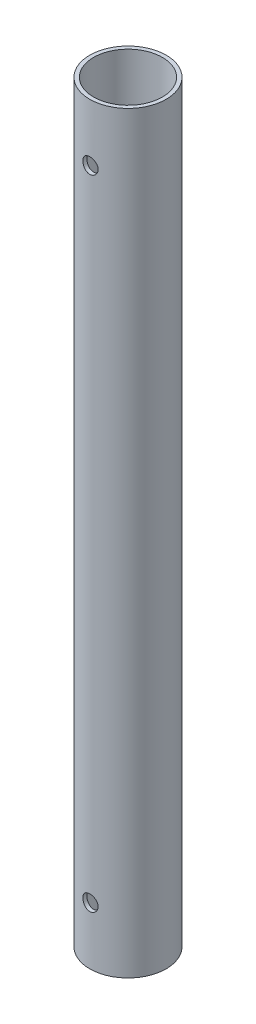
SolidWorks part; units mm, degrees
material "3.0205 (EN-AW 1200)"
ref_plane "Alzado" through (0, 0, 0) normal (0, 0, 1) x (1, 0, 0)
ref_plane "Planta" through (0, 0, 0) normal (0, 1, 0) x (1, 0, 0)
ref_plane "Vista lateral" through (0, 0, 0) normal (1, 0, 0) x (0, 0, -1)
sketch "Croquis1" plane through (0, 0, 0) normal (0, 1, 0) x (1, 0, 0)
  circle A0 centre (0, 0) radius 10
  circle A1 centre (0, 0) radius 9
  dimension "D1" = 20
  dimension "D2" = 18
extrude "Saliente-Extruir1" add sketch "Croquis1" along normal mid plane 197
sketch "Croquis2" plane through (0, 0, 0) normal (0, 0, 1) x (1, 0, 0)
  line L0 (0, 98.5) -> (0, 0) construction
  line L1 (10, 98.5) -> (-10, 98.5) construction
  line L2 (-10, -98.5) -> (10, -98.5) construction
  circle A0 centre (0, -83.5) radius 2
  circle A1 centre (0, 83.5) radius 2
  dimension "D1" = 4
  dimension "D3" = 4
  dimension "D2" = 15
  dimension "D4" = 15
extrude "Cortar-Extruir1" cut sketch "Croquis2" against normal through all both and the other way through all
